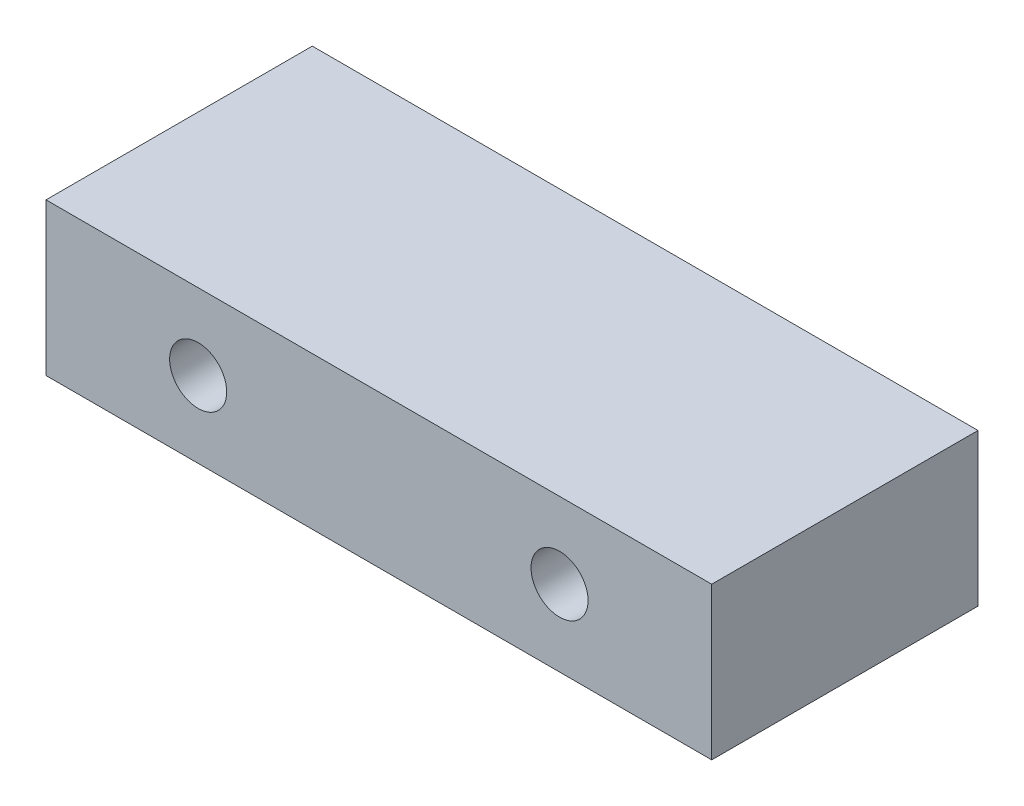
SolidWorks part; units mm, degrees
material "7075-T6, Plate (SS)"
ref_plane "Front Plane" through (0, 0, 0) normal (0, 0, 1) x (1, 0, 0)
ref_plane "Top Plane" through (0, 0, 0) normal (0, 1, 0) x (1, 0, 0)
ref_plane "Right Plane" through (0, 0, 0) normal (1, 0, 0) x (0, 0, -1)
sketch "Sketch1" plane through (0, 0, 0) normal (0, 0, 1) x (1, 0, 0)
  line L1 (-8.75, 2) -> (8.75, 2)
  line L2 (-8.75, 2) -> (-8.75, -2)
  line L3 (-8.75, -2) -> (8.75, -2)
  line L4 (8.75, 2) -> (8.75, -2)
  line L5 (-8.75, 2) -> (8.75, -2) construction
  line L6 (-8.75, -2) -> (8.75, 2) construction
  point P0 (0, 0)
  dimension "D1" = 4
  dimension "D2" = 17.5
extrude "Boss-Extrude1" add sketch "Sketch1" against normal blind 7
sketch "Sketch3" plane through (0, 0, 0) normal (0, 0, 1) x (1, 0, 0)
  line L0 (-8.75, 2) -> (-8.75, -2) construction
  line L1 (8.75, -2) -> (8.75, 2) construction
  line L2 (-8.75, -2) -> (8.75, -2) construction
  circle A0 centre (-4.75, 0) radius 0.75
  circle A1 centre (4.75, 0) radius 0.75
  dimension "D5" = 1.5
  dimension "D6" = 1.5
  dimension "D1" = 4
  dimension "D2" = 4
  dimension "D3" = 2
  dimension "D4" = 2
extrude "Cut-Extrude1" cut sketch "Sketch3" against normal up to next contours A1 | A0
